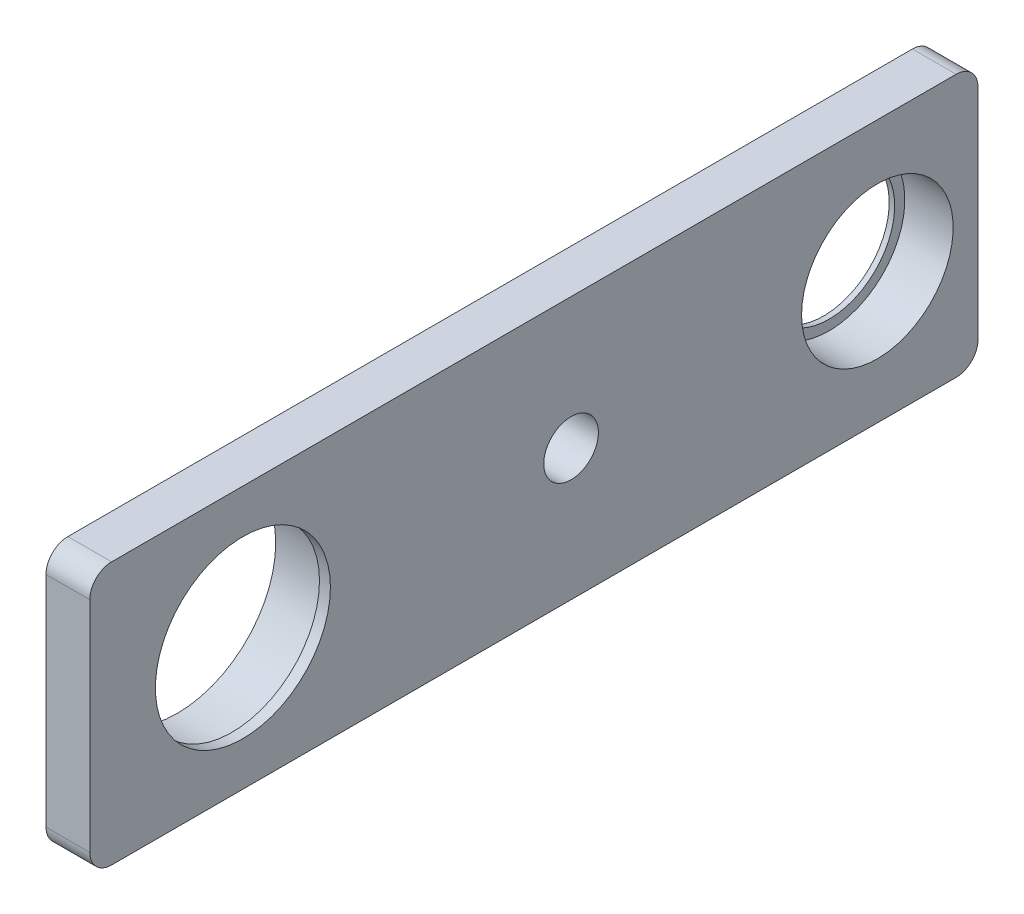
SolidWorks part; units mm, degrees
ref_plane "Front Plane" through (0, 0, 0) normal (0, 0, 1) x (1, 0, 0)
ref_plane "Top Plane" through (0, 0, 0) normal (0, 1, 0) x (1, 0, 0)
ref_plane "Right Plane" through (0, 0, 0) normal (1, 0, 0) x (0, 0, -1)
sketch "Sketch1" plane through (0, 0, 0) normal (1, 0, 0) x (0, 0, -1)
  line L0 (0, 19.05) -> (123.825, 19.05) construction
  line L1 (0, 0) -> (123.825, 0)
  line L2 (0, 0) -> (0, 38.1)
  line L3 (0, 38.1) -> (123.825, 38.1)
  line L4 (123.825, 0) -> (123.825, 38.1)
  circle A0 centre (22.225, 19.05) radius 14.2875
  circle A1 centre (69.85, 19.05) radius 3.9687
  circle A2 centre (114.3, 19.05) radius 4.7625
  dimension "D3" = 28.575
  dimension "D6" = 7.9375
  dimension "D8" = 9.525
  dimension "D1" = 38.1
  dimension "D2" = 9.525
  dimension "D4" = 22.225
  dimension "D5" = 47.625
  dimension "D7" = 44.45
extrude "Boss-Extrude1" add sketch "Sketch1" along normal blind 6.35
sketch "Sketch2" [suppressed] plane through (0, 0, 0) normal (-1, 0, 0) x (0, 0, 1)
  circle A0 centre (-22.225, 19.05) radius 14.2875 construction
  circle A1 centre (-22.225, 19.05) radius 14.2875
  circle A2 centre (-22.225, 19.05) radius 12.7
  dimension "D1" = 1.5875
extrude "Boss-Extrude2" [suppressed] add sketch "Sketch2" against normal blind 1.5875
sketch "Sketch3" plane through (6.35, 0, 0) normal (1, 0, 0) x (0, 0, -1)
  circle A0 centre (22.225, 19.05) radius 14.2875 construction
  circle A1 centre (22.225, 19.05) radius 14.2875
  circle A2 centre (22.225, 19.05) radius 12.7
  dimension "D1" = 1.5875
extrude "Boss-Extrude3" add sketch "Sketch3" against normal blind 1.5875
sketch "Sketch4" [suppressed] plane through (6.35, 0, 0) normal (1, 0, 0) x (0, 0, -1)
  circle A0 centre (22.225, 19.05) radius 14.2875 construction
  circle A1 centre (22.225, 19.05) radius 14.2875
  circle A2 centre (22.225, 19.05) radius 15.875
  dimension "D1" = 31.75
extrude "Boss-Extrude4" [suppressed] add sketch "Sketch4" along normal blind 3.175
sketch "Sketch5" plane through (0, 0, 0) normal (-1, 0, 0) x (0, 0, 1)
  circle A0 centre (-22.225, 19.05) radius 14.2875 construction
  circle A1 centre (-22.225, 19.05) radius 14.2875
  circle A2 centre (-22.225, 19.05) radius 15.875
  dimension "D1" = 31.75
extrude "Boss-Extrude5" add sketch "Sketch5" along normal blind 3.175
sketch "Sketch6" [suppressed] plane through (0, 0, -123.825) normal (0, 0, -1) x (-1, 0, 0)
  line L4 (0, 0) -> (0, 38.1)
  line L5 (0, 38.1) -> (-6.35, 38.1)
  line L6 (-6.35, 38.1) -> (-6.35, 0)
  line L7 (-6.35, 0) -> (0, 0)
  line L8 (0, 0) -> (0, 38.1)
  line L9 (0, 38.1) -> (-6.35, 38.1)
  line L10 (-6.35, 38.1) -> (-6.35, 0)
  line L11 (-6.35, 0) -> (0, 0)
  dimension "D1" = 0
extrude "Boss-Extrude6" [suppressed] add sketch "Sketch6" along normal blind 25.4
sketch "Sketch11" [suppressed] plane through (0, 0, 0) normal (-1, 0, 0) x (0, 0, 1)
  circle A0 centre (-114.3, 19.05) radius 22.05 construction
  dimension "D1" = 44.1
sketch "Sketch14" [suppressed] plane through (0, 0, 0) normal (-1, 0, 0) x (0, 0, 1)
  line L0 (0, 0) -> (-149.225, 0) construction
  line L1 (-149.225, 38.1) -> (0, 38.1) construction
  line L2 (0, 0) -> (-149.225, 0)
  line L3 (-149.225, 38.1) -> (0, 38.1)
  circle A0 centre (-114.3, 19.05) radius 28.575
  dimension "D1" = 57.15
extrude "Boss-Extrude7" [suppressed] add sketch "Sketch14" against normal up to surface (6.35 mm away) contours L3 A0 | L2 A0
hole_wizard "CSK for M4 Flat Head Machine Screw2" [suppressed] positions "Sketch12" profile "Sketch13" countersink size "M4" standard "ANSI Metric"
sketch "Sketch12" plane through (0, 0, 0) normal (-1, 0, 0) x (0, 0, 1)
  circle A0 centre (-114.3, 19.05) radius 22.05 construction
  point P0 (-92.25, 19.05)
  point P4 (-136.35, 19.05)
  point P6 (-114.3, 41.1)
  point P8 (-114.3, -3)
sketch "Sketch13" plane through (0, 19.05, -92.25) normal (0, 1, 0) x (0, 0, 1)
  line L0 (0, 0) -> (0, 14.0519)
  line L1 (0, 14.0519) -> (2.25, 12.7)
  line L2 (2.25, 12.7) -> (2.25, 2.45)
  line L3 (2.25, 2.45) -> (4.7, 0)
  line L5 (4.7, 0) -> (0, 0)
  line L6 (-2.25, 2.45) -> (-4.7, 0) construction
  line L10 (0, 14.0519) -> (-2.25, 12.7) construction
  line L11 (0, -6.35) -> (0, 107.95) construction
  dimension "Hole Dia." = 4.5
  dimension "Hole Depth" = 12.7
  dimension "Near C'Sink Dia." = 9.4
  dimension "Near C'Sink Angle" = 90
  dimension "Drill Angle" = 118
fillet "Fillet1" [suppressed] radius 3.175
sketch "Sketch15" [suppressed] plane through (6.35, 0, 0) normal (1, 0, 0) x (0, 0, -1)
  circle A0 centre (114.3, 19.05) radius 9.525
  dimension "D1" = 19.05
extrude "Cut-Extrude1" [suppressed] cut sketch "Sketch15" against normal through all
sketch "Sketch17" plane through (0, 0, -123.825) normal (0, 0, -1) x (-1, 0, 0)
  line L4 (0, 0) -> (0, 38.1)
  line L5 (0, 38.1) -> (-6.35, 38.1)
  line L6 (-6.35, 38.1) -> (-6.35, 0)
  line L7 (-6.35, 0) -> (0, 0)
  line L8 (0, 0) -> (0, 38.1)
  line L9 (0, 38.1) -> (-6.35, 38.1)
  line L10 (-6.35, 38.1) -> (-6.35, 0)
  line L11 (-6.35, 0) -> (0, 0)
  dimension "D1" = 0
extrude "Boss-Extrude8" add sketch "Sketch17" along normal blind 5.08
sketch "Sketch16" plane through (0, 0, 0) normal (-1, 0, 0) x (0, 0, 1)
  circle A0 centre (-114.3, 19.05) radius 11
  dimension "D1" = 22
extrude "Cut-Extrude3" cut sketch "Sketch16" against normal up to next
sketch "Sketch18" plane through (0, 0, 0) normal (-1, 0, 0) x (0, 0, 1)
  circle A0 centre (-114.3, 19.05) radius 11 construction
  circle A1 centre (-114.3, 19.05) radius 11
  circle A2 centre (-114.3, 19.05) radius 12.7
  dimension "D1" = 25.4
extrude "Boss-Extrude9" add sketch "Sketch18" along normal blind 0.6604
fillet "Fillet2" radius 3.175 4 edges at (3.175, 0, -128.905) (3.175, 38.1, -128.905) (3.175, 0, 0) (3.175, 38.1, 0)
sketch "Sketch19" plane through (-0.6604, 0, 0) normal (-1, 0, 0) x (0, 0, 1)
  circle A0 centre (-114.3, 19.05) radius 12.7 construction
  circle A1 centre (-114.3, 19.05) radius 12.7
  circle A2 centre (-114.3, 19.05) radius 9.525
  dimension "D1" = 19.05
extrude "Boss-Extrude10" add sketch "Sketch19" along normal blind 0.7937
